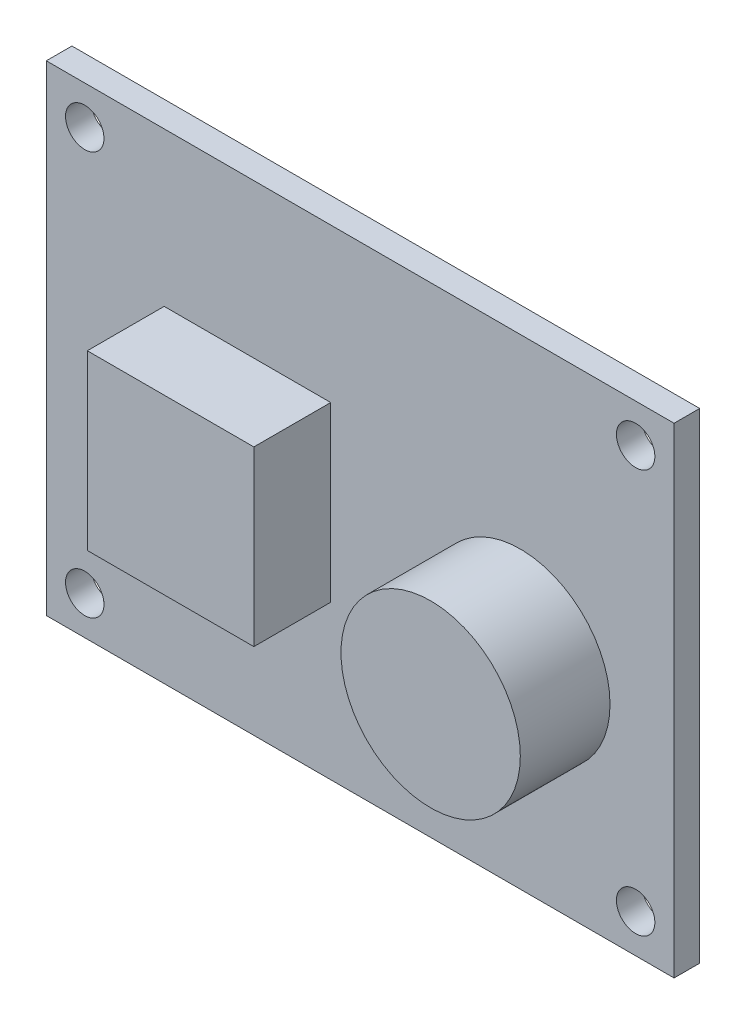
SolidWorks part; units mm, degrees
ref_plane "Спереди" through (0, 0, 0) normal (0, 0, 1) x (1, 0, 0)
ref_plane "Сверху" through (0, 0, 0) normal (0, 1, 0) x (1, 0, 0)
ref_plane "Справа" through (0, 0, 0) normal (1, 0, 0) x (0, 0, -1)
sketch "Эскиз1" plane through (0, 0, 0) normal (0, 0, 1) x (1, 0, 0)
  line L1 (-22.111, 16.0561) -> (26.889, 16.0561)
  line L2 (-22.111, 16.0561) -> (-22.111, -21.4439)
  line L3 (-22.111, -21.4439) -> (26.889, -21.4439)
  line L4 (26.889, 16.0561) -> (26.889, -21.4439)
  dimension "D1" = 49
  dimension "D2" = 37.5
extrude "Бобышка-Вытянуть1" add sketch "Эскиз1" along normal blind 2
sketch "Эскиз2" plane through (0, 0, 2) normal (0, 0, 1) x (1, 0, 0)
  line L0 (26.889, 16.0561) -> (-22.111, 16.0561) construction
  line L1 (-22.111, 16.0561) -> (-22.111, -21.4439) construction
  line L2 (26.889, -21.4439) -> (26.889, 16.0561) construction
  line L3 (-22.111, -21.4439) -> (26.889, -21.4439) construction
  circle A0 centre (-19.111, 13.0561) radius 1.5
  circle A1 centre (23.889, 13.0561) radius 1.5
  circle A2 centre (23.889, -18.4439) radius 1.5
  circle A3 centre (-19.111, -18.4439) radius 1.5
  dimension "D1" = 3
  dimension "D2" = 3
  dimension "D3" = 3
  dimension "D4" = 3
  dimension "D5" = 3
  dimension "D6" = 3
  dimension "D7" = 3
  dimension "D8" = 3
  dimension "D9" = 3
  dimension "D10" = 3
  dimension "D11" = 3
  dimension "D12" = 3
extrude "Вырез-Вытянуть1" cut sketch "Эскиз2" against normal through all
sketch "Эскиз3" plane through (0, 0, 2) normal (0, 0, 1) x (1, 0, 0)
  line L0 (-22.111, -21.4439) -> (26.889, -21.4439) construction
  line L1 (26.889, -21.4439) -> (26.889, 16.0561) construction
  circle A0 centre (14.889, -5.4439) radius 7
  dimension "D1" = 14
  dimension "D3" = 12
  dimension "D2" = 16
extrude "Бобышка-Вытянуть2" add sketch "Эскиз3" along normal blind 7
sketch "Эскиз4" plane through (0, 0, 2) normal (0, 0, 1) x (1, 0, 0)
  line L0 (-22.111, 16.0561) -> (-22.111, -21.4439) construction
  line L1 (-12.911, 4.0561) -> (0.089, 4.0561)
  line L2 (-12.911, 4.0561) -> (-12.911, -9.4439)
  line L3 (-12.911, -9.4439) -> (0.089, -9.4439)
  line L4 (0.089, 4.0561) -> (0.089, -9.4439)
  line L7 (-22.111, -21.4439) -> (26.889, -21.4439) construction
  line L9 (26.889, 16.0561) -> (-22.111, 16.0561) construction
  dimension "D1" = 13.5
  dimension "D2" = 13
  dimension "D3" = 9.2
  dimension "D4" = 12
extrude "Бобышка-Вытянуть3" add sketch "Эскиз4" along normal blind 6
